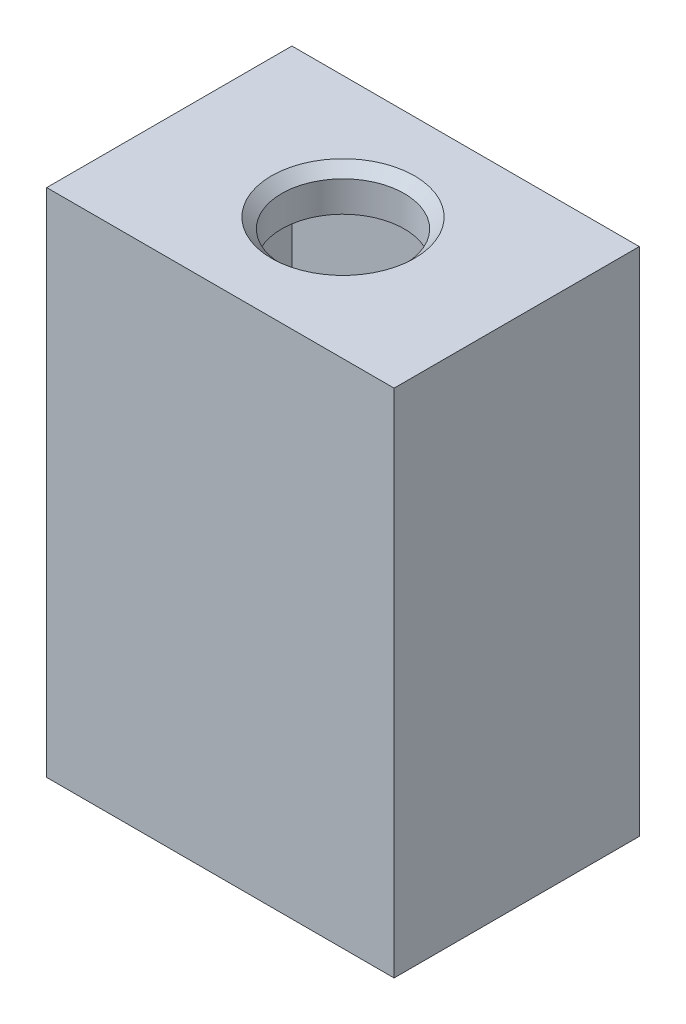
SolidWorks part; units mm, degrees
ref_plane "Front Plane" through (0, 0, 0) normal (0, 0, 1) x (1, 0, 0)
ref_plane "Top Plane" through (0, 0, 0) normal (0, 1, 0) x (1, 0, 0)
ref_plane "Right Plane" through (0, 0, 0) normal (1, 0, 0) x (0, 0, -1)
sketch "Sketch1" plane through (0, 0, 0) normal (0, 1, 0) x (1, 0, 0)
  line L1 (-8.5, 6) -> (8.5, 6)
  line L2 (-8.5, 6) -> (-8.5, -6)
  line L3 (-8.5, -6) -> (8.5, -6)
  line L4 (8.5, 6) -> (8.5, -6)
  circle A0 centre (0, 0) radius 3
  point P4 (0, 6)
  point P6 (-8.5, 0)
  dimension "D3" = 6
  dimension "D1" = 17
  dimension "D2" = 12
extrude "Boss-Extrude1" add sketch "Sketch1" along normal blind 2
sketch "Sketch2" plane through (0, 0, 0) normal (0, 1, 0) x (1, 0, 0)
  line L1 (-8.5, 6) -> (8.5, 6)
  line L2 (-8.5, 6) -> (-8.5, -6)
  line L3 (-8.5, -6) -> (8.5, -6)
  line L4 (8.5, 6) -> (8.5, -6)
  line L5 (-7, 4.5) -> (7, 4.5)
  line L6 (-7, 4.5) -> (-7, -4.5)
  line L7 (-7, -4.5) -> (7, -4.5)
  line L8 (7, 4.5) -> (7, -4.5)
  dimension "D1" = 1.5
  dimension "D2" = 1.5
  dimension "D3" = 1.5
  dimension "D4" = 1.5
extrude "Boss-Extrude2" add sketch "Sketch2" against normal blind 23
chamfer "Chamfer1" distance 0.5 angle 45 1 edges at (0, 2, 3)
